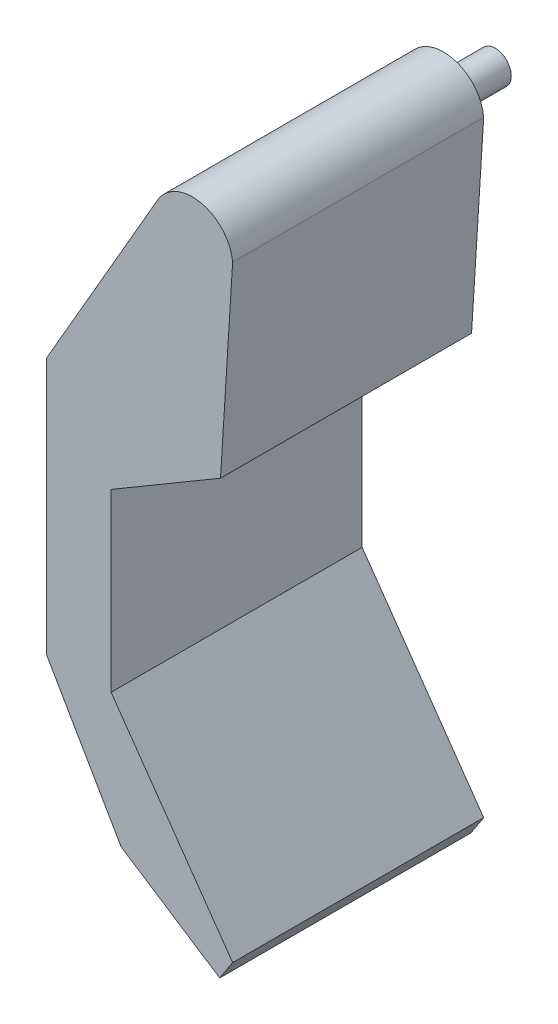
SolidWorks part; units mm, degrees
ref_plane "前视基准面" through (0, 0, 0) normal (0, 0, 1) x (1, 0, 0)
ref_plane "上视基准面" through (0, 0, 0) normal (0, 1, 0) x (1, 0, 0)
ref_plane "右视基准面" through (0, 0, 0) normal (1, 0, 0) x (0, 0, -1)
sketch "草图1" plane through (0, 0, 0) normal (0, 0, 1) x (1, 0, 0)
  line L0 (0.4413, 66.8945) -> (-16.8792, 36.8945)
  line L1 (-16.8792, 36.8945) -> (-16.8792, -3.1055)
  line L2 (-16.8792, -3.1055) -> (-5.3322, -23.1055)
  line L5 (-7.0008, 37.5151) -> (-6.8792, 37.579)
  line L26 (-5.3322, -23.1055) -> (9.9927, -33.1055)
  line L27 (11.9998, 64.1907) -> (10.1143, 34.1907)
  line L28 (10.1143, 34.1907) -> (-6.8792, 24.1907)
  line L29 (-6.8792, 24.1907) -> (-6.8792, 14.1907)
  line L32 (-6.8792, 14.1907) -> (-6.8792, -3.1055)
  line L35 (-6.8792, -3.1055) -> (11.9998, -30.0298)
  line L36 (11.9998, -30.0298) -> (9.9927, -33.1055)
  arc A4 (0.4413, 66.8945) -> (11.9998, 64.1907) centre (5.7669, 63.6033) cw
  dimension "D7" = 30
  dimension "D8" = 10
  dimension "D9" = 10
  dimension "D6" = 10
  dimension "D1" = 150
  dimension "D2" = 150
  dimension "D3" = 30
  dimension "D4" = 40
  dimension "D5" = 20
  dimension "D10" = 10
sketch "草图2" plane through (0, 0, 0) normal (0, 0, 1) x (1, 0, 0)
  circle A2 centre (5.7844, 63.8812) radius 2.5
  dimension "D1" = 5
extrude "凸台-拉伸4" add sketch "草图1" along normal blind 39
ref_plane "基准面1" through (0.4413, 66.8945, 0) normal (0, 0, -1) x (-1, 0, 0)
extrude "凸台-拉伸5" add sketch "草图2" against normal blind 8 contours A2
